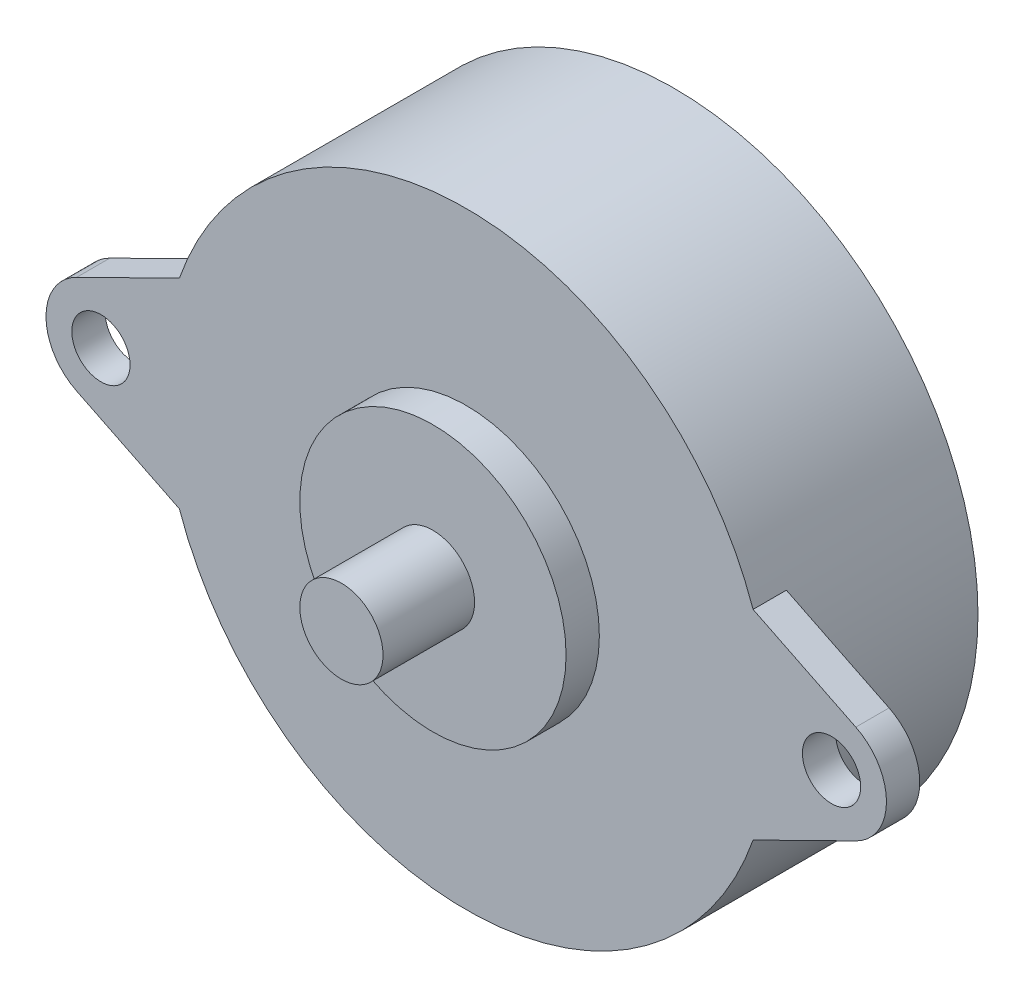
SolidWorks part; units mm, degrees
material "1060 Alloy"
ref_plane "Front Plane" through (0, 0, 0) normal (0, 0, 1) x (1, 0, 0)
ref_plane "Top Plane" through (0, 0, 0) normal (0, 1, 0) x (1, 0, 0)
ref_plane "Right Plane" through (0, 0, 0) normal (1, 0, 0) x (0, 0, -1)
sketch "Sketch1" plane through (0, 0, 0) normal (0, 0, 1) x (1, 0, 0)
  circle A0 centre (0, 0) radius 18.25
  dimension "D1" = 36.5
extrude "Boss-Extrude1" add sketch "Sketch1" along normal blind 12.5
sketch "Sketch2" plane through (0, 0, 12.5) normal (0, 0, 1) x (1, 0, 0)
  line L0 (-21.95, 0) -> (21.95, 0) construction
  line L1 (-23.4079, 2.9605) -> (-17.2355, 6)
  line L2 (-23.4079, -2.9605) -> (-17.2355, -6)
  line L3 (23.4079, 2.9605) -> (17.2355, 6)
  line L4 (23.4079, -2.9605) -> (17.2355, -6)
  circle A0 centre (-21.95, 0) radius 1.75
  circle A1 centre (21.95, 0) radius 1.75
  arc A2 (-23.4079, 2.9605) -> (-23.4079, -2.9605) centre (-21.95, 0) ccw
  arc A3 (23.4079, 2.9605) -> (23.4079, -2.9605) centre (21.95, 0) cw
  circle A4 centre (0, 0) radius 18.25 construction
  arc A5 (-17.2355, 6) -> (-17.2355, -6) centre (0, 0) ccw
  arc A6 (17.2355, 6) -> (17.2355, -6) centre (0, 0) cw
  point P4 (0, 0)
  point P26 (-25.25, 0)
  point P27 (25.25, 0)
  point P28 (-18.25, 0)
  dimension "D1" = 3.5
  dimension "D2" = 3.5
  dimension "D3" = 43.9
  dimension "D4" = 50.5
  dimension "D5" = 12
extrude "Boss-Extrude2" add sketch "Sketch2" against normal blind 2
sketch "Sketch3" plane through (0, 0, 12.5) normal (0, 0, 1) x (1, 0, 0)
  circle A0 centre (0, 0) radius 8
  dimension "D1" = 16
extrude "Boss-Extrude3" add sketch "Sketch3" along normal blind 2
sketch "Sketch4" plane through (0, 0, 14.5) normal (0, 0, 1) x (1, 0, 0)
  circle A0 centre (0, 0) radius 2.5
  dimension "D1" = 5
extrude "Boss-Extrude4" add sketch "Sketch4" along normal blind 5.5
